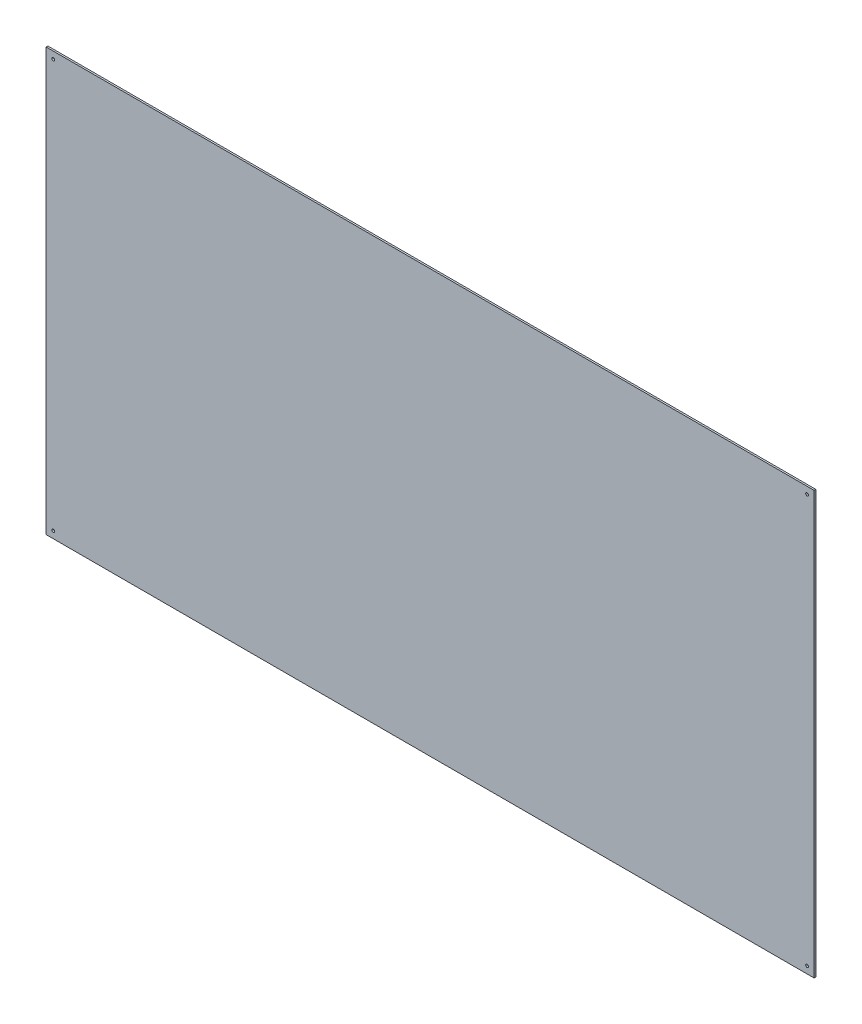
SolidWorks part; units mm, degrees
ref_plane "前视基准面" through (0, 0, 0) normal (0, 0, 1) x (1, 0, 0)
ref_plane "上视基准面" through (0, 0, 0) normal (0, 1, 0) x (1, 0, 0)
ref_plane "右视基准面" through (0, 0, 0) normal (1, 0, 0) x (0, 0, -1)
sketch "草图1" plane through (0, 0, 0) normal (0, 0, 1) x (1, 0, 0)
  line L0 (0, 456.417) -> (0, -472.6064) construction
  line L1 (-1068.4913, 0) -> (959.0191, 0) construction
  line L3 (-1100, 605) -> (1100, 605)
  line L4 (-1100, 605) -> (-1100, -605)
  line L5 (-1100, -605) -> (1100, -605)
  line L6 (1100, 605) -> (1100, -605)
  dimension "D1" = 2200
  dimension "D2" = 1210
extrude "凸台-拉伸1" add sketch "草图1" along normal blind 5
sketch "草图3" plane through (0, 0, 5) normal (0, 0, 1) x (1, 0, 0)
  line L0 (1100, 605) -> (-1100, 605) construction
  line L1 (-1100, 605) -> (-1100, -605) construction
  line L2 (2.75, 0) -> (-2.75, 0) construction
  line L3 (0, -2.75) -> (0, 2.75) construction
  circle A0 centre (-1080, 585) radius 4.05
  circle A1 centre (-1080, -585) radius 4.05
  circle A2 centre (1080, -585) radius 4.05
  circle A3 centre (1080, 585) radius 4.05
  point P6 (-1095.5492, 583.5349)
  dimension "D1" = 20
  dimension "D2" = 20
extrude "切除-拉伸1" cut sketch "草图3" against normal blind 5
